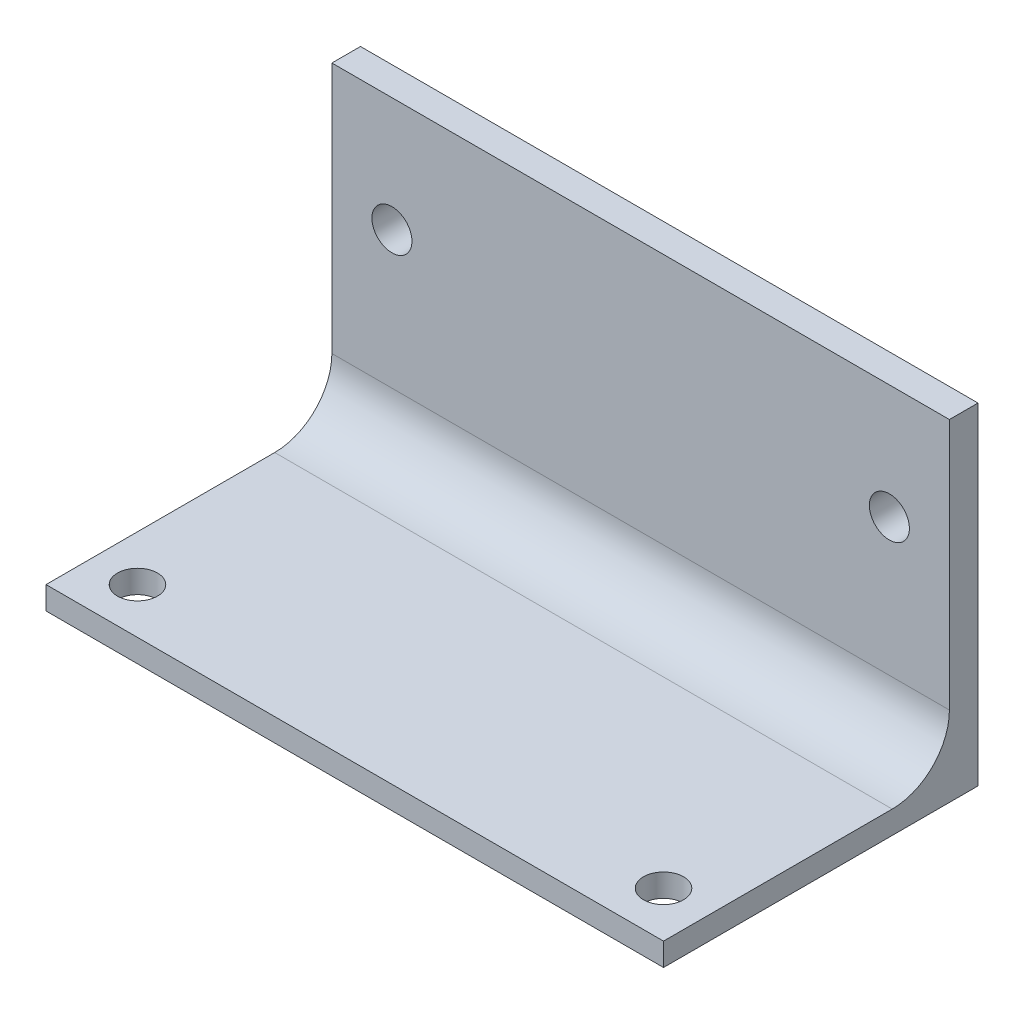
SolidWorks part; units mm, degrees
ref_plane "Front Plane" through (0, 0, 0) normal (0, 0, 1) x (1, 0, 0)
ref_plane "Top Plane" through (0, 0, 0) normal (0, 1, 0) x (1, 0, 0)
ref_plane "Right Plane" through (0, 0, 0) normal (1, 0, 0) x (0, 0, -1)
sketch "Sketch1" plane through (0, 0, 0) normal (0, 1, 0) x (1, 0, 0)
  line L1 (0, 0) -> (54, 0)
  line L2 (0, 0) -> (0, 25)
  line L3 (0, 25) -> (54, 25)
  line L4 (54, 0) -> (54, 25)
  circle A0 centre (4, 4) radius 1.75
  circle A1 centre (50, 4) radius 1.75
  point P9 (0, 0)
  dimension "D2" = 3.5
  dimension "D1" = 46
  dimension "D3" = 25
  dimension "D4" = 4
  dimension "D5" = 4
  dimension "D6" = 4
extrude "Boss-Extrude1" add sketch "Sketch1" along normal blind 2
sketch "Sketch2" plane through (0, 2, 0) normal (0, 1, 0) x (1, 0, 0)
  line L0 (54, 0) -> (54, 25) construction
  line L1 (0, 25) -> (54, 25)
  line L2 (0, 25) -> (0, 27.5)
  line L3 (0, 27.5) -> (54, 27.5)
  line L4 (54, 25) -> (54, 27.5)
  dimension "D1" = 2.5
extrude "Boss-Extrude2" add sketch "Sketch2" along normal blind 27 separate body
sketch "Sketch3" plane through (0, 2, 0) normal (0, -1, 0) x (1, 0, 0)
  line L4 (0, -25) -> (0, -27.5)
  line L5 (0, -27.5) -> (54, -27.5)
  line L6 (54, -27.5) -> (54, -25)
  line L7 (54, -25) -> (0, -25)
  line L8 (0, -25) -> (0, -27.5)
  line L9 (0, -27.5) -> (54, -27.5)
  line L10 (54, -27.5) -> (54, -25)
  line L11 (54, -25) -> (0, -25)
  dimension "D1" = 0
extrude "Boss-Extrude3" add sketch "Sketch3" along normal up to surface (2 mm away) up to face at (4, 0, -2.25)
sketch "Sketch4" plane through (0, 0, -25) normal (0, 0, 1) x (1, 0, 0)
  line L0 (7, 19) -> (47, 19) construction
  line L1 (5.25, 19) -> (0, 19) construction
  line L2 (0, 29) -> (0, 2) construction
  line L3 (48.75, 19) -> (54, 19) construction
  line L4 (54, 29) -> (54, 2) construction
  line L5 (0, 29) -> (54, 29) construction
  circle A0 centre (5.25, 19) radius 1.75
  circle A1 centre (48.75, 19) radius 1.75
  dimension "D2" = 3.5
  dimension "D1" = 40
  dimension "D3" = 10
extrude "Cut-Extrude1" cut sketch "Sketch4" against normal blind 27
fillet "Fillet1" radius 5 1 edges at (27, 2, -25)
